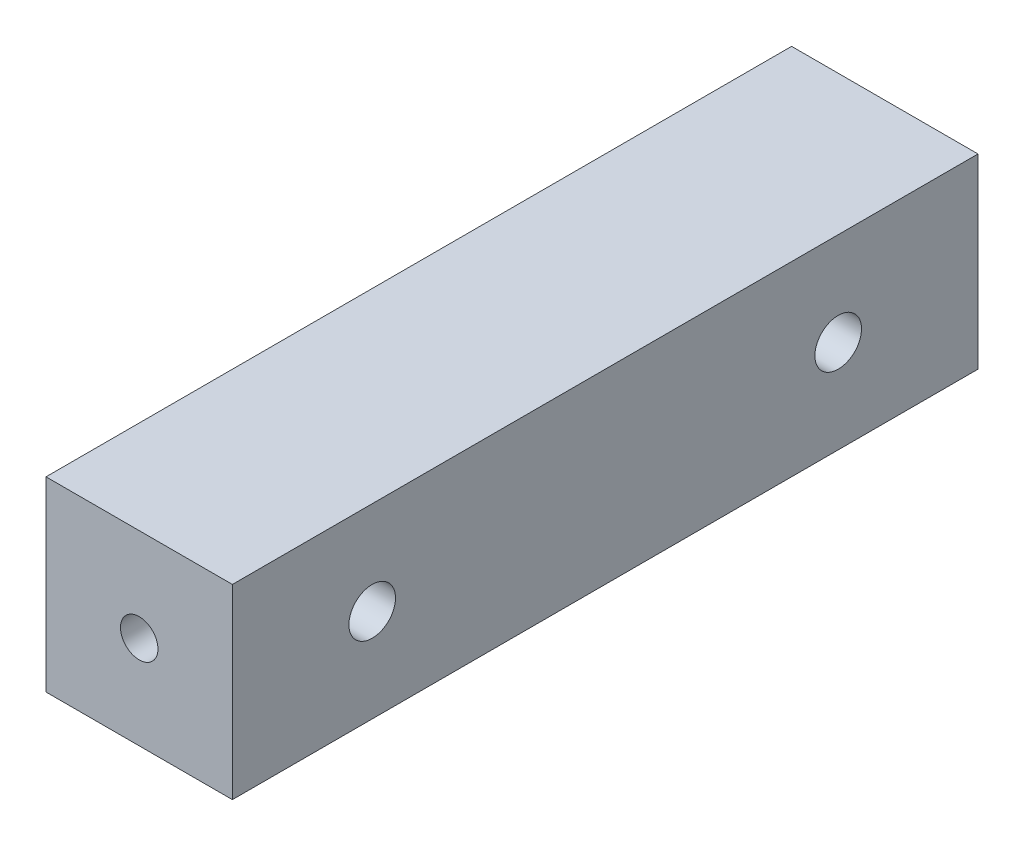
SolidWorks part; units mm, degrees
material "6061-T6 (SS)"
ref_plane "Front" through (0, 0, 0) normal (0, 0, 1) x (1, 0, 0)
ref_plane "Top" through (0, 0, 0) normal (0, 1, 0) x (1, 0, 0)
ref_plane "Right" through (0, 0, 0) normal (1, 0, 0) x (0, 0, -1)
sketch "Sketch1" plane through (0, 0, 0) normal (0, 0, 1) x (1, 0, 0)
  line L1 (-12.7, -12.7) -> (12.7, -12.7)
  line L2 (-12.7, -12.7) -> (-12.7, 12.7)
  line L3 (-12.7, 12.7) -> (12.7, 12.7)
  line L4 (12.7, -12.7) -> (12.7, 12.7)
  line L5 (-12.7, -12.7) -> (12.7, 12.7) construction
  line L6 (-12.7, 12.7) -> (12.7, -12.7) construction
  point P0 (0, 0)
  dimension "D1" = 25.4
  dimension "D2" = 25.4
extrude "Boss-Extrude1" add sketch "Sketch1" along normal mid plane 101.6
sketch "Sketch2" plane through (0, 0, 50.8) normal (0, 0, 1) x (1, 0, 0)
  circle A0 centre (0, 0) radius 2.5527
  dimension "D1" = 5.1054
extrude "Cut-Extrude1" cut sketch "Sketch2" against normal blind 12.7
sketch "Sketch3" plane through (0, 0, -50.8) normal (0, 0, -1) x (-1, 0, 0)
  circle A0 centre (0, 0) radius 2.5527
  dimension "D1" = 5.1054
extrude "Cut-Extrude2" cut sketch "Sketch3" against normal blind 12.7
sketch "Sketch4" plane through (12.7, 0, 0) normal (1, 0, 0) x (0, 0, -1)
  line L0 (-31.75, 0) -> (0, 0) construction
  line L1 (0, 0) -> (31.75, 0) construction
  circle A0 centre (-31.75, 0) radius 3.175
  circle A1 centre (31.75, 0) radius 3.175
  point P4 (2.6386, 0)
  point P7 (0, 0)
  point P8 (-21.0943, 0)
  point P9 (0, 0)
  point P11 (17.0332, 0)
  dimension "D1" = 6.35
  dimension "D2" = 6.35
  dimension "D3" = 31.75
  dimension "D4" = 31.75
extrude "Cut-Extrude3" cut sketch "Sketch4" against normal through all
